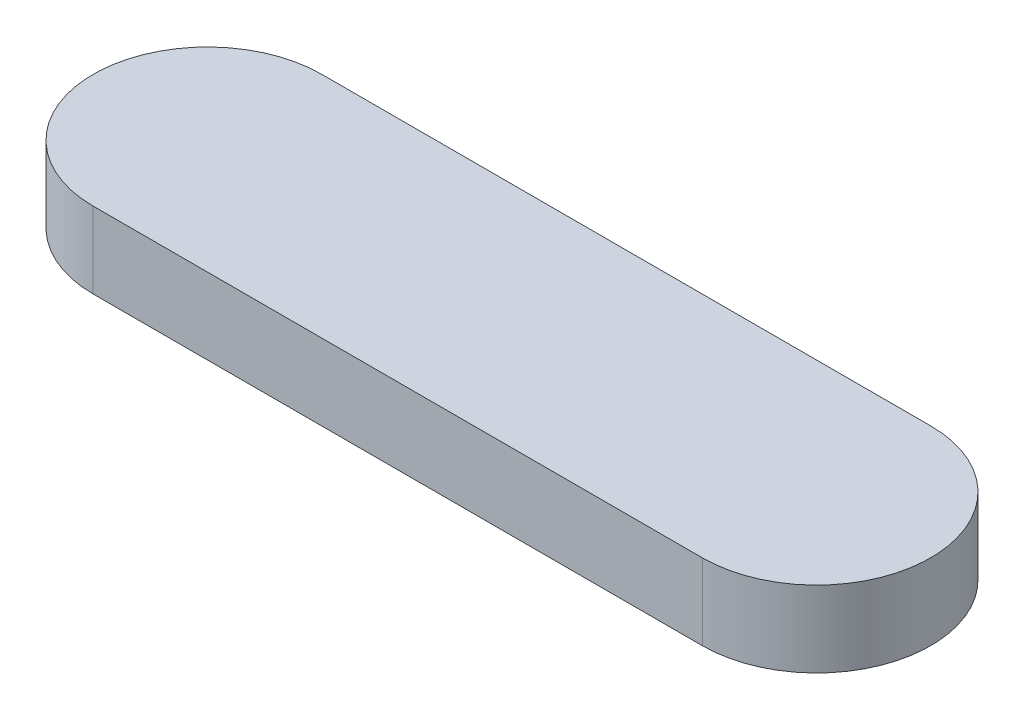
SolidWorks part; units mm, degrees
ref_plane "前视基准面" through (0, 0, 0) normal (0, 0, 1) x (1, 0, 0)
ref_plane "上视基准面" through (0, 0, 0) normal (0, 1, 0) x (1, 0, 0)
ref_plane "右视基准面" through (0, 0, 0) normal (1, 0, 0) x (0, 0, -1)
other "Configuration Table"
sketch "草图1" plane through (0, 0, 0) normal (0, 1, 0) x (1, 0, 0)
  line L0 (0, 0) -> (400, 0) construction
  line L1 (0, 75) -> (400, 75)
  line L2 (0, -75) -> (400, -75)
  arc A0 (0, 75) -> (0, -75) centre (0, 0) ccw
  arc A1 (400, -75) -> (400, 75) centre (400, 0) ccw
  point P3 (200, 0)
  dimension "D2" = 75
  dimension "D1" = 400
extrude "凸台-拉伸1" add sketch "草图1" along normal blind 50
